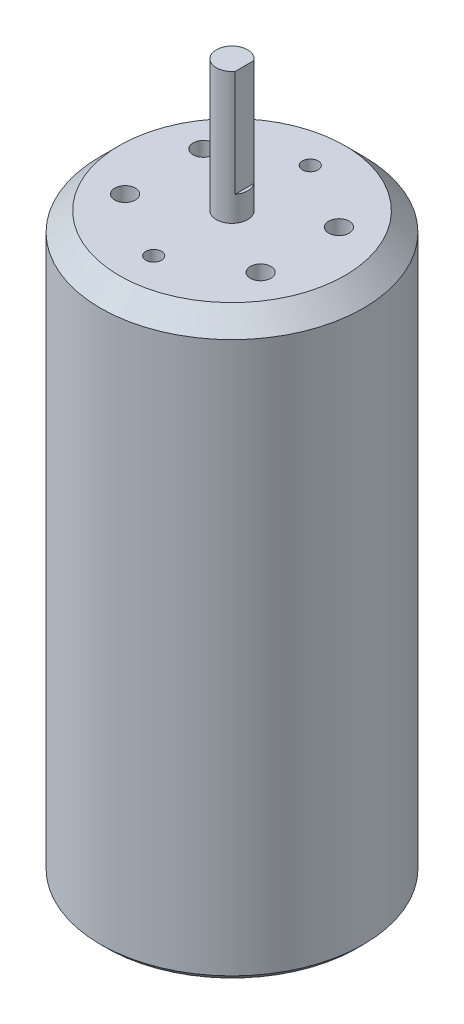
SolidWorks part; units mm, degrees
ref_plane "Front Plane" through (0, 0, 0) normal (0, 0, 1) x (1, 0, 0)
ref_plane "Top Plane" through (0, 0, 0) normal (0, 1, 0) x (1, 0, 0)
ref_plane "Right Plane" through (0, 0, 0) normal (1, 0, 0) x (0, 0, -1)
sketch "Sketch1" plane through (0, 0, 0) normal (0, 0, 1) x (1, 0, 0)
  line L0 (0, 0) -> (0, 124.9132) construction
  line L1 (0, 0) -> (0, 113)
  line L2 (0, 113) -> (2.5, 113)
  line L3 (2.5, 113) -> (2.5, 92)
  line L4 (2.5, 92) -> (21, 92)
  line L5 (21, 92) -> (21, 0)
  line L6 (21, 0) -> (0, 0)
  point P3 (0, 124.9132)
  point P9 (3.9288, 115.6933)
  dimension "D1" = 42
  dimension "D2" = 92
  dimension "D3" = 5
  dimension "D4" = 21
revolve "Revolve1" add sketch "Sketch1" angle 360 about L0
sketch "Sketch2" plane through (0, 113, 0) normal (0, 1, 0) x (1, 0, 0)
  line L0 (2, -1.5) -> (2, 1.5)
  circle A1 centre (0, 0) radius 2.5
  arc A2 (2, -1.5) -> (2, 1.5) centre (0, 0) ccw
  circle A3 centre (0, 0) radius 2.5 construction
  dimension "D2" = 4.5
  dimension "D1" = 0
extrude "Cut-Extrude1" cut sketch "Sketch2" against normal blind 17
sketch "Sketch3" plane through (0, 92, 0) normal (0, 1, 0) x (1, 0, 0)
  line L0 (0, 12.5) -> (0, -12.5) construction
  line L1 (0, 0) -> (12.5, 0) construction
  line L2 (0, 0) -> (10.8253, 6.25) construction
  circle A0 centre (0, 0) radius 12.5
  point P7 (10.8253, -6.25)
  point P8 (-10.8253, -6.25)
  point P9 (-10.8253, 6.25)
  dimension "D1" = 25
  dimension "D2" = 30
hole_wizard "Tap Drill for M3x0.5 Tap1" positions "Sketch4" profile "Sketch6" hole size "M3x0.5" standard "ANSI Metric"
sketch "Sketch4" plane through (0, 92, 0) normal (0, 1, 0) x (1, 0, 0)
  point P0 (0, 12.5)
  point P3 (0, -12.5)
sketch "Sketch6" plane through (0, 92, -12.5) normal (1, 0, 0) x (0, 0, 1)
  line L0 (0, 0) -> (0, 10)
  line L1 (0, 10) -> (1.25, 9.2489)
  line L2 (1.25, 9.2489) -> (1.25, 0)
  line L5 (1.25, 0) -> (0, 0)
  line L10 (0, 10) -> (-1.25, 9.2489) construction
  line L11 (0, -6.35) -> (0, 107.95) construction
  dimension "Hole Dia." = 2.5
  dimension "Hole Depth" = 10
  dimension "Drill Angle" = 118
hole_wizard "Tap Drill for M4x0.7 Tap1" positions "Sketch7" profile "Sketch8" hole size "M4x0.7" standard "ANSI Metric"
sketch "Sketch7" plane through (0, 92, 0) normal (0, 1, 0) x (1, 0, 0)
  point P0 (-10.8253, 6.25)
  point P3 (-10.8253, -6.25)
  point P6 (10.8253, -6.25)
  point P9 (10.8253, 6.25)
sketch "Sketch8" plane through (-10.8253, 92, -6.25) normal (1, 0, 0) x (0, 0, 1)
  line L0 (0, 0) -> (0, 10)
  line L1 (0, 10) -> (1.65, 9.0086)
  line L2 (1.65, 9.0086) -> (1.65, 0)
  line L5 (1.65, 0) -> (0, 0)
  line L10 (0, 10) -> (-1.65, 9.0086) construction
  line L11 (0, -6.35) -> (0, 107.95) construction
  dimension "Hole Dia." = 3.3
  dimension "Hole Depth" = 10
  dimension "Drill Angle" = 118
chamfer "Chamfer1" distance 3 angle 45 1 edges at (0, 92, -21)
chamfer "Chamfer2" distance 1 angle 45 1 edges at (0, 0, -21)
